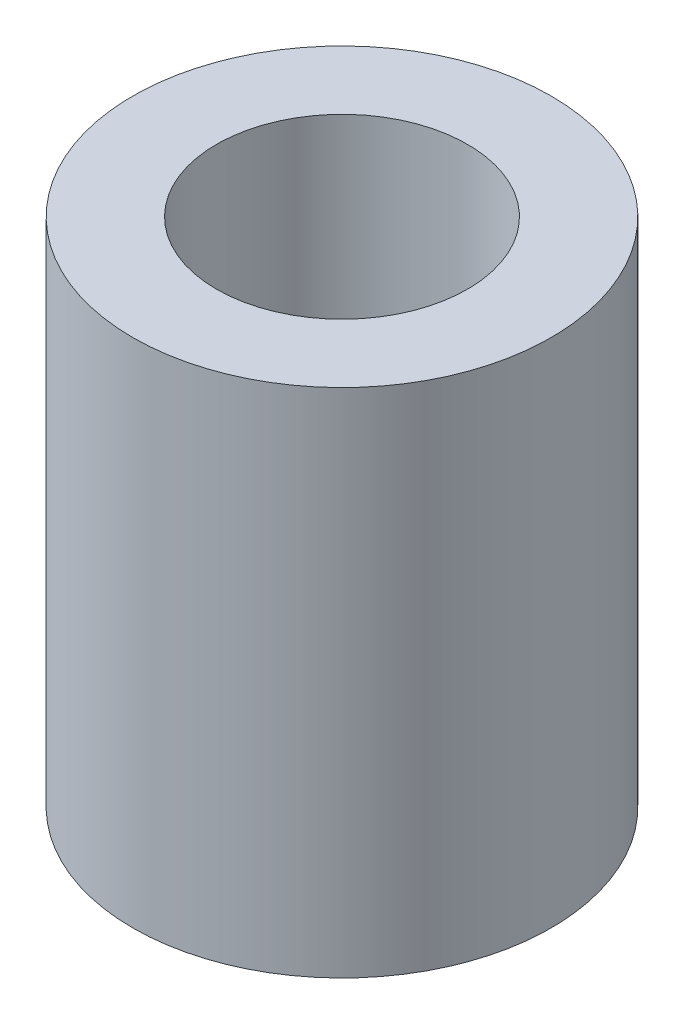
SolidWorks part; units mm, degrees
material "Polybutadiene (PB)"
ref_plane "Front Plane" through (0, 0, 0) normal (0, 0, 1) x (1, 0, 0)
ref_plane "Top Plane" through (0, 0, 0) normal (0, 1, 0) x (1, 0, 0)
ref_plane "Right Plane" through (0, 0, 0) normal (1, 0, 0) x (0, 0, -1)
sketch "Sketch1" plane through (0, 0, 0) normal (0, 1, 0) x (1, 0, 0)
  circle A0 centre (0, 0) radius 20
  circle A2 centre (0, 0) radius 12
  dimension "D1" = 40
  dimension "D2" = 24
extrude "Boss-Extrude1" add sketch "Sketch1" along normal blind 48.89
